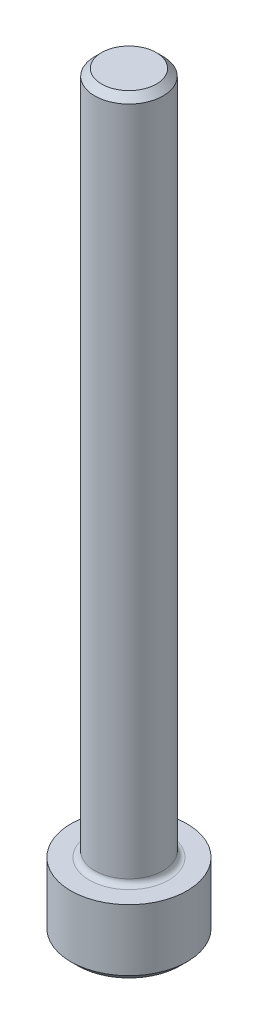
SolidWorks part; units mm, degrees
ref_plane "Front Plane" through (0, 0, 0) normal (0, 0, 1) x (1, 0, 0)
ref_plane "Top Plane" through (0, 0, 0) normal (0, 1, 0) x (1, 0, 0)
ref_plane "Right Plane" through (0, 0, 0) normal (1, 0, 0) x (0, 0, -1)
sketch "Sketch2" plane through (0, 0, 0) normal (0, 1, 0) x (1, 0, 0)
  circle A0 centre (0, 0) radius 2.5
extrude "Boss-Extrude1" add sketch "Sketch2" along normal blind 50
sketch "Sketch3" plane through (0, 0, 0) normal (0, 1, 0) x (1, 0, 0)
  circle A0 centre (0, 0) radius 4.25
extrude "Boss-Extrude2" add sketch "Sketch3" against normal blind 5
fillet "Fillet1" radius 0.4 1 edges at (0, 0, 2.5)
chamfer "Chamfer1" distance 0.5 angle 45 2 edges at (0, 50, 2.5) (0, -5, 4.25)
sketch "Sketch4" plane through (0, -5, 0) normal (0, -1, 0) x (1, 0, 0)
  line L1 (0, 2.3094) -> (-2, 1.1547)
  line L2 (-2, 1.1547) -> (-2, -1.1547)
  line L3 (-2, -1.1547) -> (0, -2.3094)
  line L4 (0, -2.3094) -> (2, -1.1547)
  line L5 (2, -1.1547) -> (2, 1.1547)
  line L6 (2, 1.1547) -> (0, 2.3094)
  circle A0 centre (0, 0) radius 2 construction
extrude "Cut-Extrude1" cut sketch "Sketch4" against normal blind 2.5
